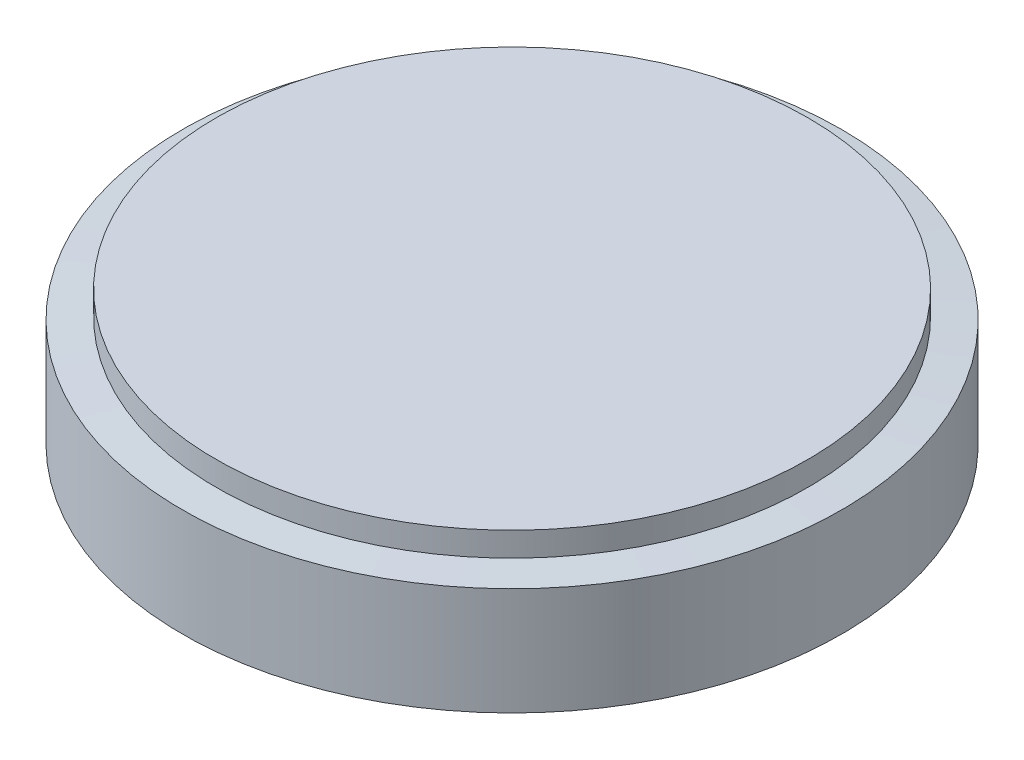
SolidWorks part; units mm, degrees
material "普通碳钢"
ref_plane "前视基准面" through (0, 0, 0) normal (0, 0, 1) x (1, 0, 0)
ref_plane "上视基准面" through (0, 0, 0) normal (0, 1, 0) x (1, 0, 0)
ref_plane "右视基准面" through (0, 0, 0) normal (1, 0, 0) x (0, 0, -1)
other "Configuration Table"
sketch "草图3" plane through (0, 0, 0) normal (0, 0, 1) x (1, 0, 0)
  line L0 (0, 0) -> (-11, 0)
  line L1 (0, 0) -> (0, 111.2724) construction
  line L2 (-11, 0) -> (-11, 5)
  line L3 (-11, 5) -> (0, 5)
  line L4 (0, 0) -> (0, 5)
  dimension "D1" = 11
  dimension "D2" = 5
revolve "旋转1" add sketch "草图3" angle 360 about L1
sketch "草图4" plane through (0, 0, 0) normal (0, 0, 1) x (1, 0, 0)
  line L0 (-12.25, 0) -> (-11, 0)
  line L1 (-12.25, 0) -> (-12.25, 4)
  line L2 (0, 0) -> (-11, 0) construction
  line L3 (-11, 0) -> (11, 0) construction
  line L4 (-11, 0) -> (-11, 4.1)
  line L5 (-11, 5) -> (-11, 0) construction
  line L6 (-11, 4.1) -> (-12.25, 4)
  line L7 (0, 0) -> (0, 4.7819) construction
revolve "旋转2" add sketch "草图4" angle 360 about L7
